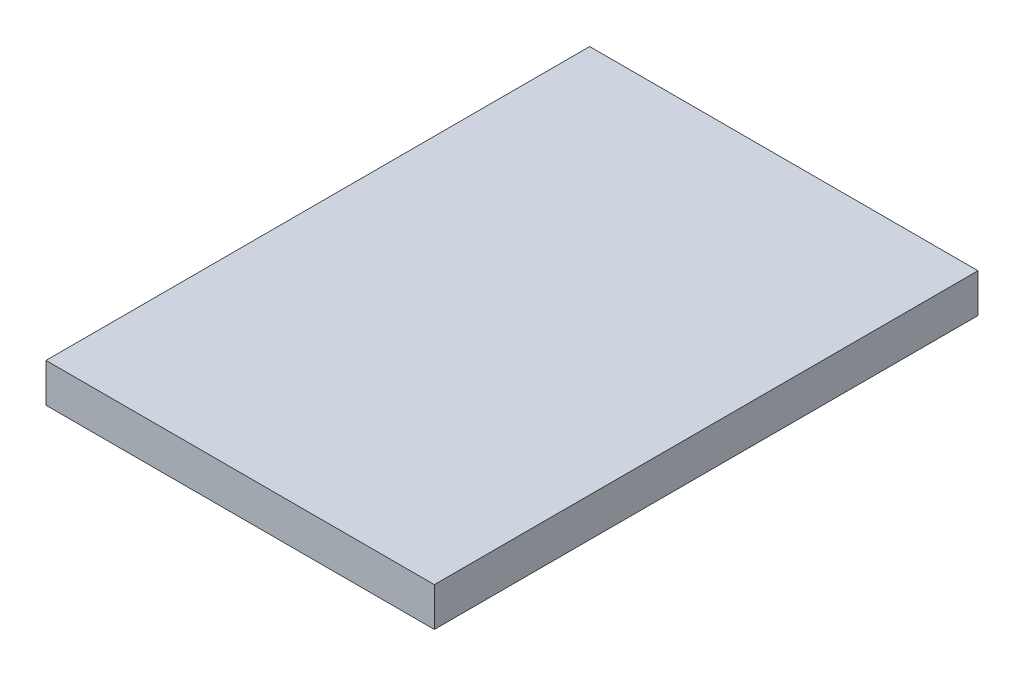
SolidWorks part; units mm, degrees
ref_plane "Front Plane" through (0, 0, 0) normal (0, 0, 1) x (1, 0, 0)
ref_plane "Top Plane" through (0, 0, 0) normal (0, 1, 0) x (1, 0, 0)
ref_plane "Right Plane" through (0, 0, 0) normal (1, 0, 0) x (0, 0, -1)
sketch "Sketch1" plane through (0, 0, 0) normal (0, 1, 0) x (1, 0, 0)
  line L1 (-10, -14) -> (10, -14)
  line L2 (-10, -14) -> (-10, 14)
  line L3 (-10, 14) -> (10, 14)
  line L4 (10, -14) -> (10, 14)
  line L5 (-10, -14) -> (10, 14) construction
  line L6 (-10, 14) -> (10, -14) construction
  point P0 (0, 0)
  dimension "D1" = 20
  dimension "D2" = 28
extrude "Boss-Extrude1" add sketch "Sketch1" along normal mid plane 2
